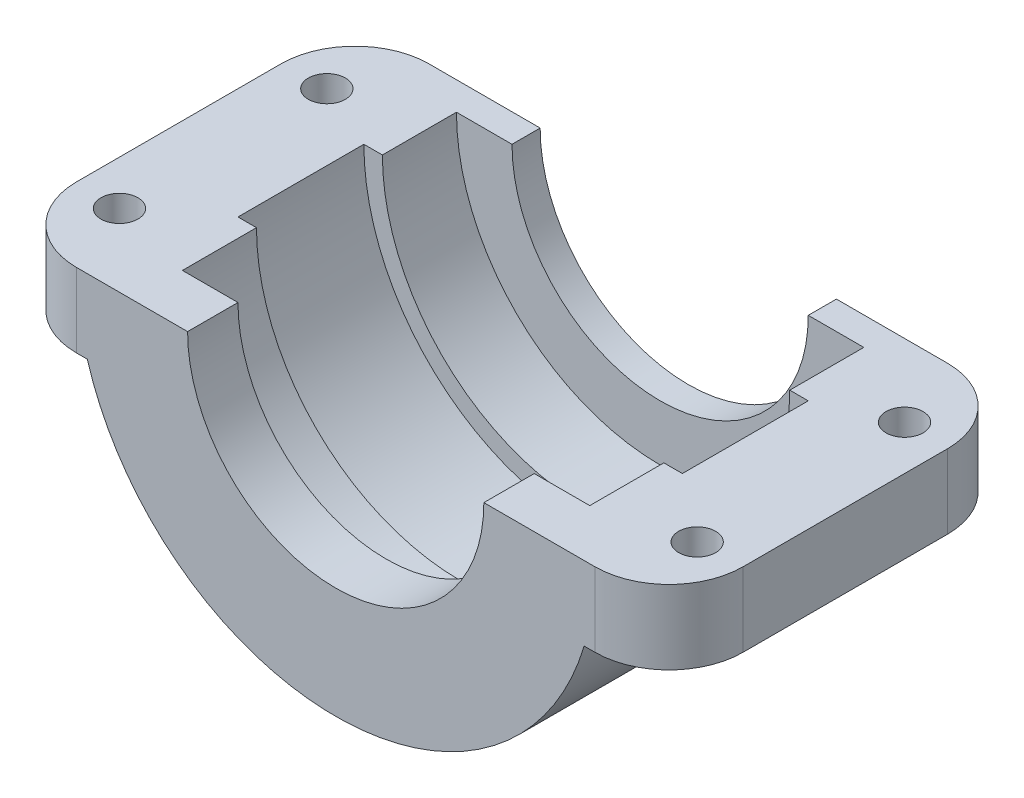
SolidWorks part; units mm, degrees
ref_plane "Alzado" through (0, 0, 0) normal (0, 0, 1) x (1, 0, 0)
ref_plane "Planta" through (0, 0, 0) normal (0, 1, 0) x (1, 0, 0)
ref_plane "Vista lateral" through (0, 0, 0) normal (1, 0, 0) x (0, 0, -1)
sketch "Croquis1" plane through (0, 0, 0) normal (0, 0, 1) x (1, 0, 0)
  circle A0 centre (0, 0) radius 35
  dimension "D1" = 70
extrude "Saliente-Extruir1" add sketch "Croquis1" along normal blind 47.6
sketch "Croquis2" plane through (0, 0, 47.6) normal (0, 0, 1) x (1, 0, 0)
  line L1 (-35, 0) -> (46.1002, 0)
  line L2 (-35, 0) -> (-35, 55.2296)
  line L3 (-35, 55.2296) -> (46.1002, 55.2296)
  line L4 (46.1002, 0) -> (46.1002, 55.2296)
  circle A0 centre (0, 0) radius 35 construction
extrude "Cortar-Extruir1" cut sketch "Croquis2" against normal through all
sketch "Croquis3" plane through (0, 0, 47.6) normal (0, 0, 1) x (1, 0, 0)
  line L0 (-35, 0) -> (35, 0) construction
  line L1 (-45, 0) -> (45, 0)
  line L2 (-45, 0) -> (-45, -10)
  line L3 (-45, -10) -> (45, -10)
  line L4 (45, 0) -> (45, -10)
  point P4 (0, 0)
  point P7 (0, 0)
  dimension "D1" = 10
  dimension "D2" = 90
  dimension "D3" = 45
  dimension "D4" = 0
extrude "Saliente-Extruir2" add sketch "Croquis3" against normal blind 47.6
sketch "Croquis4" plane through (0, 0, 0) normal (0, 1, 0) x (1, 0, 0)
  line L0 (45, 0) -> (45, -47.6) construction
  line L1 (-45, 0) -> (45, 0) construction
  line L2 (0, 0) -> (0, -47.6) construction
  line L3 (-45, -47.6) -> (45, -47.6) construction
  line L4 (0, -23.8) -> (45, -23.8) construction
  circle A0 centre (39, -9.8) radius 2.5
  circle A1 centre (39, -37.8) radius 2.5
  circle A2 centre (-39, -37.8) radius 2.5
  circle A3 centre (-39, -9.8) radius 2.5
  dimension "D1" = 5
  dimension "D2" = 6
  dimension "D3" = 9.8
extrude "Cortar-Extruir2" cut sketch "Croquis4" against normal through all
sketch "Croquis5" plane through (0, 0, 0) normal (0, 0, -1) x (-1, 0, 0)
  circle A0 centre (0, 0) radius 20
  dimension "D1" = 40
extrude "Cortar-Extruir3" cut sketch "Croquis5" against normal through all
fillet "Redondeo1" radius 10 4 edges at (-45, -5, 47.6) (-45, -5, 0) (45, -5, 47.6) (45, -5, 0)
sketch "Croquis6" plane through (0, 0, 47.6) normal (0, 0, 1) x (1, 0, 0)
  circle A0 centre (0, 0) radius 27.5
  dimension "D1" = 55
extrude "Cortar-Extruir4" cut sketch "Croquis6" against normal blind 37 from offset 6.8 offset against normal yes
sketch "Croquis7" plane through (0, 0, 40.8) normal (0, 0, -1) x (-1, 0, 0)
  circle A0 centre (0, 0) radius 30
  dimension "D1" = 60
extrude "Cortar-Extruir5" cut sketch "Croquis7" along normal blind 17 from offset 10
